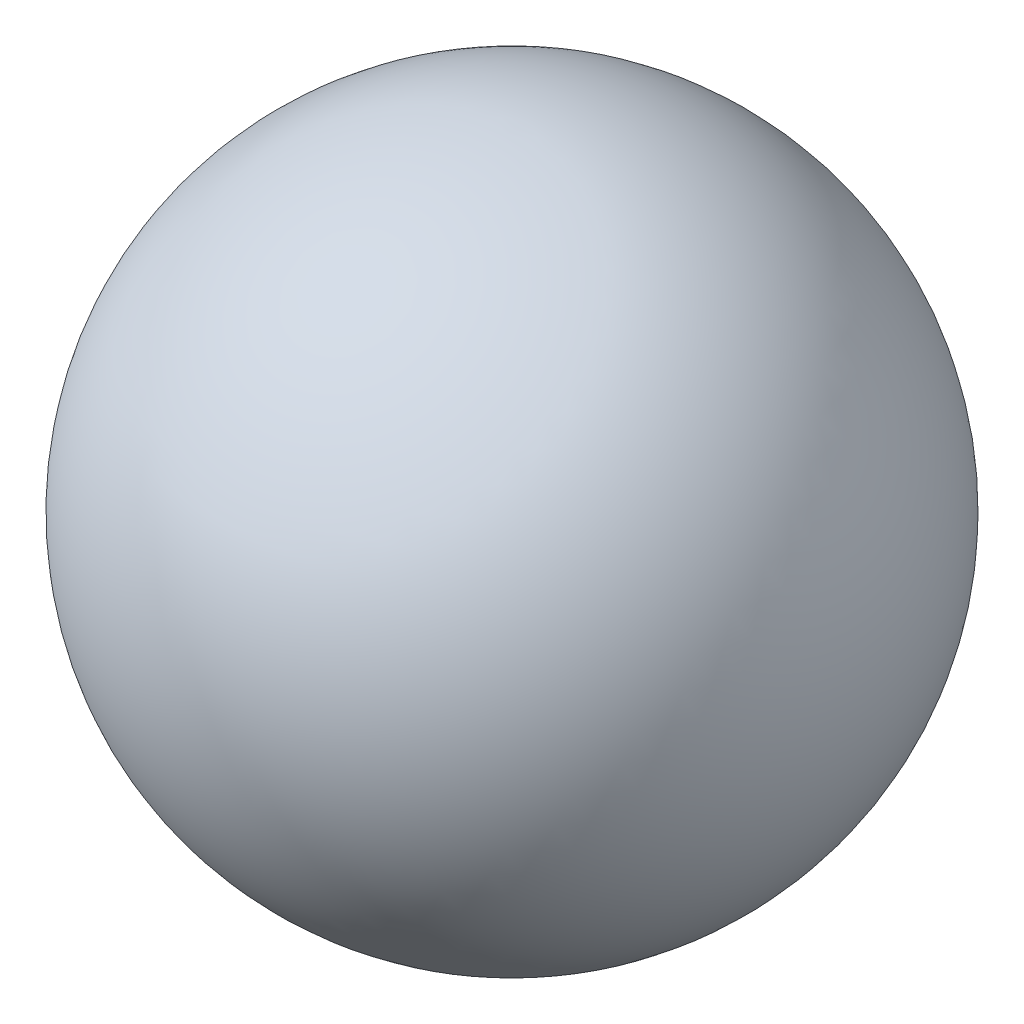
SolidWorks part; units mm, degrees
ref_plane "Front Plane" through (0, 0, 0) normal (0, 0, 1) x (1, 0, 0)
ref_plane "Top Plane" through (0, 0, 0) normal (0, 1, 0) x (1, 0, 0)
ref_plane "Right Plane" through (0, 0, 0) normal (1, 0, 0) x (0, 0, -1)
sketch "Sketch4" plane through (0, 0, 0) normal (1, 0, 0) x (0, 0, -1)
  line L0 (-1.4343, 51.0646) -> (1.4343, -51.0646)
  arc A0 (1.4343, -51.0646) -> (-1.4343, 51.0646) centre (0, 0) ccw
revolve "Revolve1" add sketch "Sketch4" angle 360 about L0
